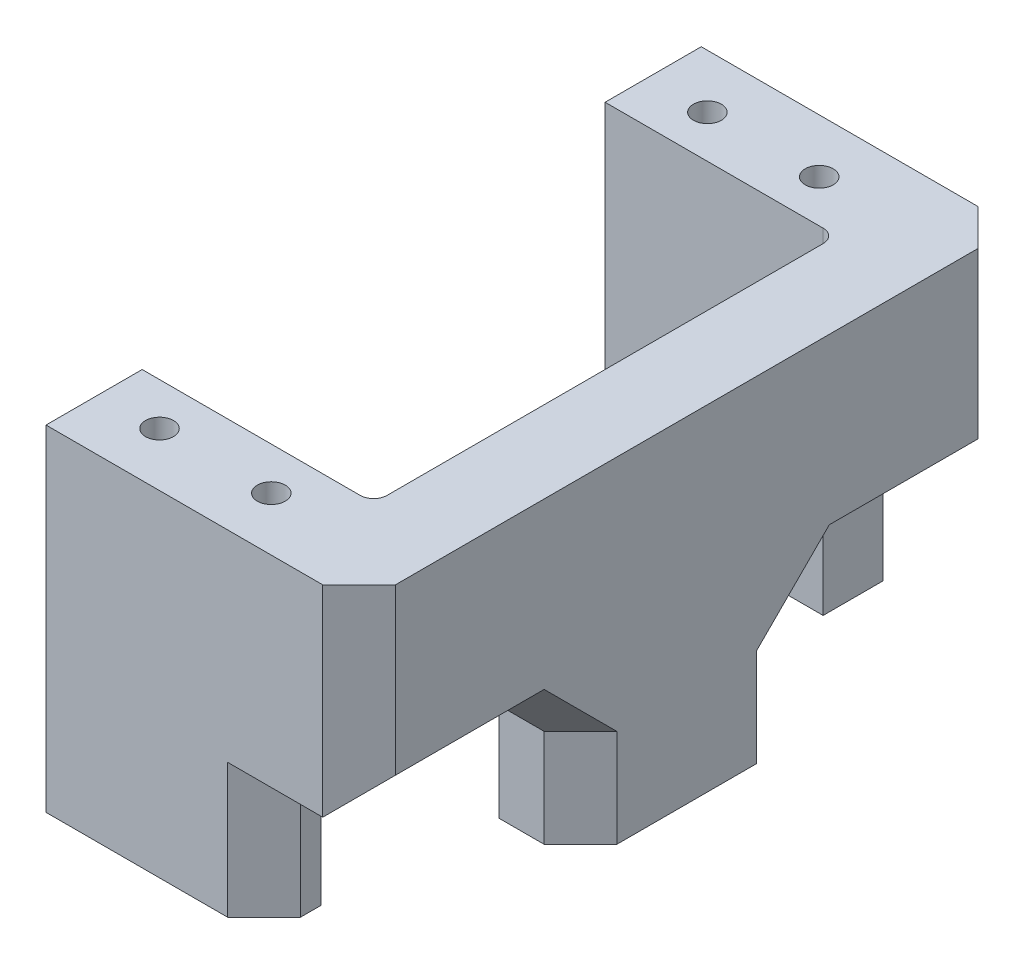
SolidWorks part; units mm, degrees
material "PET"
ref_plane "Plan de face" through (0, 0, 0) normal (0, 0, 1) x (1, 0, 0)
ref_plane "Plan de dessus" through (0, 0, 0) normal (0, 1, 0) x (1, 0, 0)
ref_plane "Plan de droite" through (0, 0, 0) normal (1, 0, 0) x (0, 0, -1)
sketch "Esquisse1" plane through (0, 0, 0) normal (0, 1, 0) x (1, 0, 0)
  line L0 (-9.5, 20.7) -> (-9.5, 29.3)
  line L1 (-9.5, 29.3) -> (18.5, 29.3)
  line L2 (18.5, 29.3) -> (18.5, -29.3)
  line L3 (18.5, -29.3) -> (-9.5, -29.3)
  line L4 (-9.5, -29.3) -> (-9.5, -20.7)
  line L5 (-9.5, -20.7) -> (10, -20.7)
  line L6 (11.2, -19.5) -> (11.2, 19.5)
  line L7 (10, 20.7) -> (-9.5, 20.7)
  line L8 (-8.3, -20.5) -> (10, -20.5) construction
  line L9 (11, -19.5) -> (11, 19.5) construction
  line L10 (10, 20.5) -> (-8.3, 20.5) construction
  line L11 (-9.5, -20.5) -> (10, -20.5) construction
  line L12 (11, -19.5) -> (11, 19.5) construction
  line L13 (10, 20.5) -> (-9.5, 20.5) construction
  line L14 (-9.5, 25) -> (18.5, 25) construction
  line L15 (-9.5, -25) -> (18.5, -25) construction
  arc A0 (10, -20.7) -> (11.2, -19.5) centre (10, -19.5) ccw
  arc A1 (11.2, 19.5) -> (10, 20.7) centre (10, 19.5) ccw
  arc A2 (10, -20.5) -> (11, -19.5) centre (10, -19.5) ccw construction
  arc A3 (11, 19.5) -> (10, 20.5) centre (10, 19.5) ccw construction
  arc A4 (10, -20.5) -> (11, -19.5) centre (10, -19.5) ccw construction
  arc A5 (11, 19.5) -> (10, 20.5) centre (10, 19.5) ccw construction
  point P10 (18.5, 0)
  point P11 (-17.32, 34.9758)
  point P12 (-17.5773, -35.2399)
  dimension "D1" = 9.5
  dimension "D2" = 0.2
  dimension "D3" = 50
  dimension "D4" = 28
extrude "Boss.-Extru.1" add sketch "Esquisse1" along normal blind 30
sketch "Esquisse2" plane through (0, 0, 0) normal (0, -1, 0) x (1, 0, 0)
  line L0 (-9.5, 20.7) -> (-9.5, 29.3) construction
  line L1 (18.5, 29.3) -> (10, 29.3)
  line L2 (18.5, 29.3) -> (18.5, 9.5)
  line L3 (18.5, 9.5) -> (10, 9.5)
  line L4 (10, 29.3) -> (10, 9.5)
  line L5 (-17.7333, 0) -> (16.2166, 0) construction
  line L6 (10, -29.3) -> (10, -9.5)
  line L7 (18.5, -9.5) -> (10, -9.5)
  line L8 (18.5, -29.3) -> (18.5, -9.5)
  line L9 (18.5, -29.3) -> (10, -29.3)
  dimension "D1" = 19
  dimension "D2" = 19.5
extrude "Enlèv. mat.-Extru.1" cut sketch "Esquisse2" against normal blind 12
hole_wizard "Trou taraudé M31" positions "Esquisse6" profile "Esquisse5" tap size "M3" standard "ISO"
sketch "Esquisse6" plane through (0, 0, 0) normal (0, -1, 0) x (-1, 0, 0)
  line L0 (-11.2, -9.5) -> (-18.5, -9.5) construction
  line L5 (9.5, 29.3) -> (9.5, 20.7) construction
  line L6 (-18.5, -9.5) -> (-11.2, -9.5) construction
  point P0 (-1, 23)
  point P2 (-14.85, 0)
  point P4 (-1, -27)
  point P9 (-14.85, -9.5)
  point P29 (-1, -25.011)
  dimension "D1" = 10.5
  dimension "D2" = 50
  dimension "D3" = 9.5
  dimension "D4" = 23
cosmetic thread "Filetage de perçage1" parameters "D1"=6, "D2"=3
cosmetic thread "Filetage de perçage2" parameters "D1"=6, "D2"=3
cosmetic thread "Filetage de perçage3" parameters "D1"=6, "D2"=3
sketch "Esquisse5" plane through (1, 0, -23) normal (1, 0, 0) x (0, 0, -1)
  line L0 (0, 0) -> (0, 10.7511)
  line L1 (0, 10.7511) -> (1.25, 10)
  line L2 (1.25, 10) -> (1.25, 0)
  line L5 (1.25, 0) -> (0, 0)
  line L10 (0, 10.7511) -> (-1.25, 10) construction
  line L11 (0, -6.35) -> (0, 107.95) construction
  dimension "Diamètre du trou pour taraudage" = 2.5
  dimension "Profondeur du trou pour taraudage" = 10
  dimension "Angle de pointe" = 118
sketch "Esquisse7" plane through (0, 30, 0) normal (0, 1, 0) x (1, 0, 0)
  line L0 (21.2214, 0) -> (-14.9227, 0) construction
  line L1 (18.5, -29.3) -> (18.5, 29.3) construction
  line L2 (-9.5, -20.7) -> (18.5, -20.7)
  line L3 (-9.5, -20.7) -> (-9.5, -29)
  line L4 (-9.5, -29) -> (18.5, -29)
  line L5 (18.5, -20.7) -> (18.5, -29)
  line L6 (18.5, 20.7) -> (18.5, 29)
  line L7 (-9.5, 29) -> (18.5, 29)
  line L8 (-9.5, 20.7) -> (-9.5, 29)
  line L9 (-9.5, 20.7) -> (18.5, 20.7)
  dimension "D1" = 58
extrude "Boss.-Extru.2" add sketch "Esquisse7" against normal up to surface (18 mm away) up to face at (13.2748, 12, 19.6748)
chamfer "Chanfrein3" distance 3.25 angle 45 10 edges at (14.85, 12, -9.5) (14.85, 12, 9.5) (18.5, 21, 29.3) (18.5, 21, -29.3) (10, 6, 29.3) (10, 6, -29.3) (18.5, 12, -19.4) (18.5, 6, -9.5) (18.5, 12, 19.4) (18.5, 6, 9.5)
hole_wizard "Trou taraudé M32" positions "Esquisse9" profile "Esquisse8" tap size "M3" standard "ISO"
sketch "Esquisse9" plane through (0, 30, 0) normal (0, 1, 0) x (1, 0, 0)
  point P14 (-4.15, 24.5)
  point P17 (-4.15, -24.5)
  point P20 (5.85, -24.5)
  point P23 (5.85, 24.5)
cosmetic thread "Filetage de perçage4" parameters "D1"=6, "D2"=3
cosmetic thread "Filetage de perçage5" parameters "D1"=6, "D2"=3
sketch "Esquisse8" plane through (-4.15, 30, -24.5) normal (1, 0, 0) x (0, 0, 1)
  line L0 (0, 0) -> (0, 10.7511)
  line L1 (0, 10.7511) -> (1.25, 10)
  line L2 (1.25, 10) -> (1.25, 0)
  line L5 (1.25, 0) -> (0, 0)
  line L10 (0, 10.7511) -> (-1.25, 10) construction
  line L11 (0, -6.35) -> (0, 107.95) construction
  dimension "Diamètre du trou pour taraudage" = 2.5
  dimension "Profondeur du trou pour taraudage" = 10
  dimension "Angle de pointe" = 118
cosmetic thread "Filetage de perçage6" parameters "D1"=6, "D2"=3
cosmetic thread "Filetage de perçage7" parameters "D1"=6, "D2"=3
sketch "Esquisse10" plane through (0, 0, 0) normal (0, -1, 0) x (1, 0, 0)
  line L0 (10, 26.05) -> (10, 20.7) construction
  line L1 (-9.5, 20.7) -> (10, 20.7)
  line L2 (-9.5, 20.7) -> (-9.5, 24.2)
  line L3 (-9.5, 24.2) -> (10, 24.2)
  line L4 (10, 20.7) -> (10, 24.2)
  dimension "D1" = 3.5
extrude "Enlèv. mat.-Extru.2" cut sketch "Esquisse10" against normal blind 10
chamfer "Chanfrein4" distance 1 angle 45 2 edges at (0.25, 10, 20.7) (0.25, 10, 24.2)
